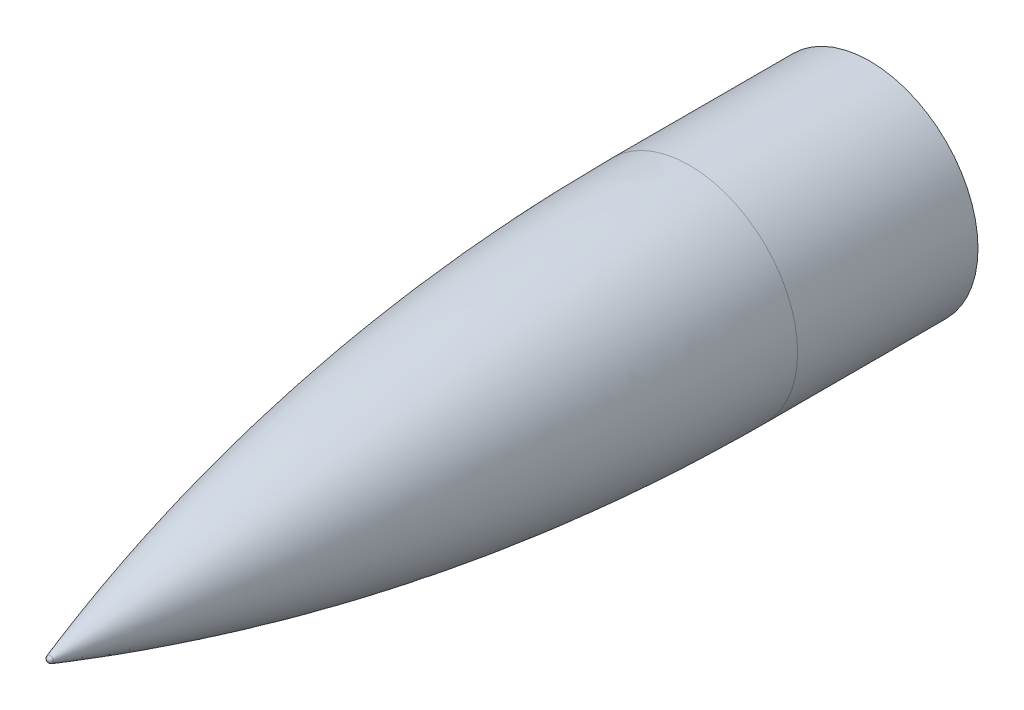
SolidWorks part; units mm, degrees
ref_plane "Front Plane" through (0, 0, 0) normal (0, 0, 1) x (1, 0, 0)
ref_plane "Top Plane" through (0, 0, 0) normal (0, 1, 0) x (1, 0, 0)
ref_plane "Right Plane" through (0, 0, 0) normal (1, 0, 0) x (0, 0, -1)
sketch "Sketch1" plane through (0, 0, 0) normal (1, 0, 0) x (0, 0, -1)
  line L0 (457.2, 76.2) -> (457.2, 0)
  line L3 (5.3527, 0) -> (457.2, 0)
  arc A0 (7.0817, 2.407) -> (5.3527, 0) centre (7.8927, 0) ccw
  spline S0 degree 4 poles (-35.6796, -12.7715) (-34.7813, -12.4363) (-32.9942, -11.771) (-30.2893, -10.7703) (-26.7141, -9.4577) (-23.1087, -8.1462) (-19.5793, -6.8716) (-15.9626, -5.5786) (-12.5222, -4.356) (-8.8089, -3.052) (-5.5383, -1.9077) (-1.5252, -0.5238) (1.2621, 0.4365) (5.8879, 2.0052) (7.8157, 2.6553) (11.3287, 3.8322) (13.3283, 4.496) (15.6063, 5.2499) (17.8085, 5.9745) (20.4143, 6.827) (23.3765, 7.7887) (26.3498, 8.7467) (29.3366, 9.7018) (32.3447, 10.6563) (35.3697, 11.6087) (38.4141, 12.5597) (42.2218, 13.7396) (46.7955, 15.1418) (52.1375, 16.7575) (58.251, 18.5765) (64.3727, 20.3677) (70.5024, 22.1312) (81.2432, 25.1688) (96.6262, 29.3693) (125.9605, 36.953) (169.4827, 46.9527) (219.6115, 56.5749) (270.0987, 64.0718) (308.124, 68.4345) (331.9399, 70.6586) (344.6532, 71.7106) (354.1927, 72.4421) (363.7365, 73.116) (374.8766, 73.8183) (386.0226, 74.4197) (395.5799, 74.8631) (403.5463, 75.1846) (409.9206, 75.4129) (415.4988, 75.5875) (420.281, 75.7191) (424.2657, 75.8167) (427.0567, 75.8788) (429.4458, 75.9274) (431.8248, 75.9722) (434.1709, 76.0131) (436.9321, 76.0555) (440.0149, 76.097) (443.1959, 76.1315) (446.2128, 76.1591) (449.5189, 76.1799) (452.2733, 76.1937) (456.4001, 76.2009) (458.4614, 76.2004) (463.2503, 76.191) (466.2953, 76.1712) (471.3281, 76.1343) (476.6605, 76.0702) (482.4571, 75.9811) (487.9691, 75.8669) (492.7464, 75.7545) (496.0254, 75.6663) (498.9009, 75.5843) (500.7847, 75.5263) (501.7363, 75.4964) (502.213, 75.4812) knots 0 0 0 0 0 0.006978 0.013955 0.020933 0.027911 0.034763 0.041614 0.048466 0.055317 0.062169 0.069021 0.075872 0.082724 0.088413 0.094101 0.096946 0.09979 0.105479 0.111168 0.116857 0.122545 0.128234 0.134048 0.139862 0.145676 0.15149 0.163118 0.174746 0.186373 0.198001 0.209629 0.221257 0.267769 0.31428 0.430559 0.546838 0.639861 0.686372 0.709628 0.721256 0.732884 0.756139 0.779395 0.802651 0.814279 0.825907 0.837534 0.849162 0.854976 0.86079 0.866604 0.869511 0.872418 0.878107 0.883796 0.889484 0.895173 0.900862 0.906551 0.912239 0.917928 0.924725 0.931522 0.938319 0.945117 0.958711 0.972305 0.979229 0.986152 0.993076 0.996538 1 1 1 1 1 construction
  spline S1 degree 4 poles (7.0817, 2.407) (7.6992, 2.6151) (8.9579, 3.038) (11.3287, 3.8322) (13.3283, 4.496) (15.6063, 5.2499) (17.8085, 5.9745) (20.4143, 6.827) (23.3765, 7.7887) (26.3498, 8.7467) (29.3366, 9.7018) (32.3447, 10.6563) (35.3697, 11.6087) (38.4141, 12.5597) (42.2218, 13.7396) (46.7955, 15.1418) (52.1375, 16.7575) (58.251, 18.5765) (64.3727, 20.3677) (70.5024, 22.1312) (81.2432, 25.1688) (96.6262, 29.3693) (125.9605, 36.953) (169.4827, 46.9527) (219.6115, 56.5749) (270.0987, 64.0718) (308.124, 68.4345) (331.9399, 70.6586) (344.6532, 71.7106) (354.1927, 72.4421) (363.7365, 73.116) (374.8766, 73.8183) (386.0226, 74.4197) (395.5799, 74.8631) (403.5463, 75.1846) (409.9206, 75.4129) (415.4988, 75.5875) (420.281, 75.7191) (424.2657, 75.8167) (427.0567, 75.8788) (429.4458, 75.9274) (431.8248, 75.9722) (434.1709, 76.0131) (436.9321, 76.0555) (440.0149, 76.097) (443.1959, 76.1315) (446.2128, 76.1591) (449.5189, 76.1799) (452.2733, 76.1937) (455.2246, 76.1988) (456.5484, 76.2) (457.2, 76.2) knots 0.082724 0.082724 0.082724 0.082724 0.082724 0.088413 0.094101 0.096946 0.09979 0.105479 0.111168 0.116857 0.122545 0.128234 0.134048 0.139862 0.145676 0.15149 0.163118 0.174746 0.186373 0.198001 0.209629 0.221257 0.267769 0.31428 0.430559 0.546838 0.639861 0.686372 0.709628 0.721256 0.732884 0.756139 0.779395 0.802651 0.814279 0.825907 0.837534 0.849162 0.854976 0.86079 0.866604 0.869511 0.872418 0.878107 0.883796 0.889484 0.895173 0.900862 0.906551 0.912239 0.917928 0.917928 0.917928 0.917928 0.917928
  dimension "D1" = 2.54
ref_axis "Axis1" through (0, 0, -480.06) along (0, 0, 1)
revolve "Revolve1" add sketch "Sketch1" angle 360 about axis through (0, 0, -480.06) along (0, 0, 1)
sketch "Sketch4" plane through (0, 0, -457.2) normal (0, 0, -1) x (-1, 0, 0)
  circle A0 centre (0, 0) radius 76.2
  dimension "D1" = 152.4
extrude "Boss-Extrude1" add sketch "Sketch4" along normal blind 127
equation "\"BodyTubeRadius\"= 3in"
equation "\"OgiveRatio\"= 3"
equation "\"OgiveRadius\"= ( \"BodyTubeRadius\" ^ 2 + ( \"OgiveLength\" ) ^ 2 ) / ( 2 * \"BodyTubeRadius\" )"
equation "\"OgiveLength\"= 2 * \"BodyTubeRadius\" * \"OgiveRatio\""
equation "\"noseRadius\"= .1in"
equation "\"noseCapCenter\"= \"OgiveLength\" - sqr ( ( \"OgiveRadius\" - \"noseRadius\" ) ^ 2 - ( \"OgiveRadius\" - \"BodyTubeRadius\" ) ^ 2 )'center of the sphere that forms that cap"
equation "\"yTangent\"= ( \"noseRadius\" * ( \"OgiveRadius\" - \"BodyTubeRadius\" ) ) / ( \"OgiveRadius\" - \"noseRadius\" )'y location of tangency"
equation "\"xTangent\"= \"noseCapCenter\" - sqr ( \"noseRadius\" ^ 2 - \"yTangent\" ^ 2 )'x location of tangency"
equation "\"D1@Sketch4\"=\"BodyTubeRadius\"*2"
equation "\"BodyTubeLength\"= 5in"
equation "\"D1@Sketch1\"=\"noseRadius\""
